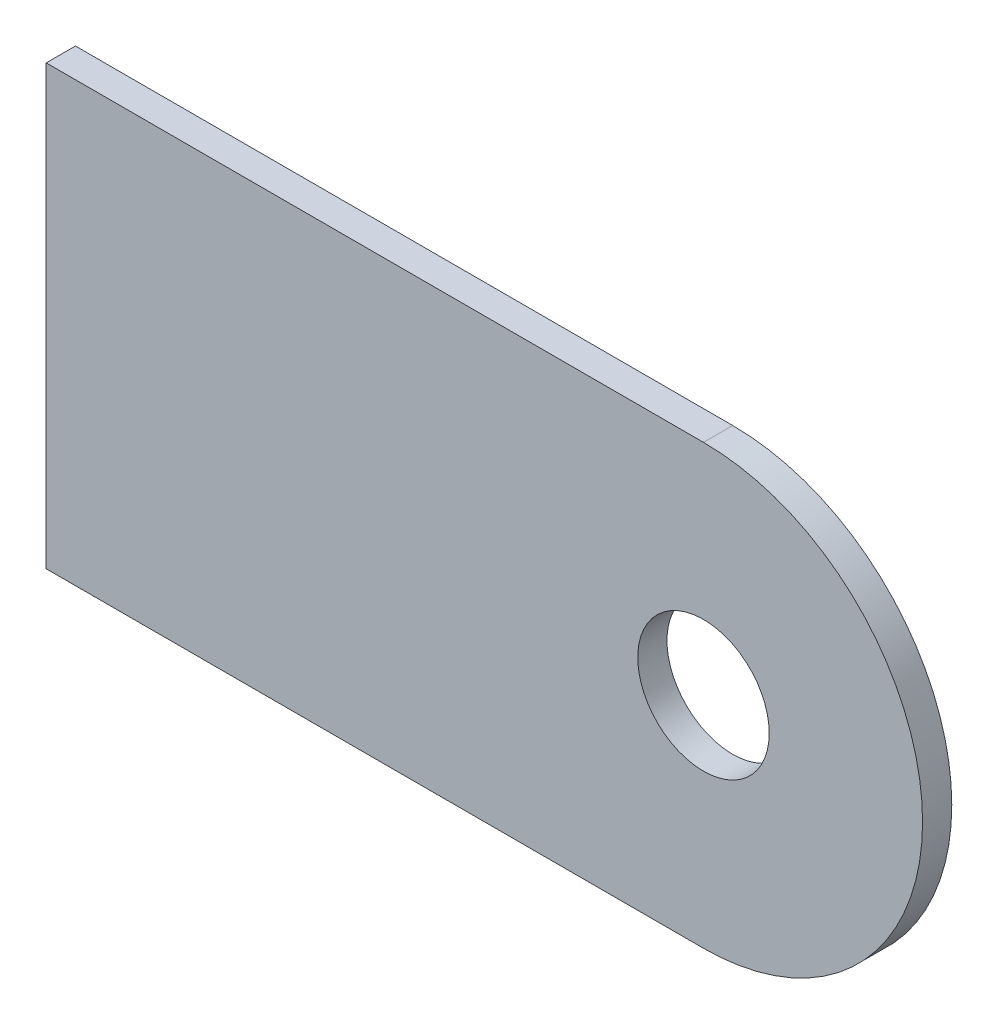
SolidWorks part; units mm, degrees
ref_plane "前视基准面" through (0, 0, 0) normal (0, 0, 1) x (1, 0, 0)
ref_plane "上视基准面" through (0, 0, 0) normal (0, 1, 0) x (1, 0, 0)
ref_plane "右视基准面" through (0, 0, 0) normal (1, 0, 0) x (0, 0, -1)
other "Configuration Table"
sketch "草图1" plane through (0, 0, 0) normal (0, 0, 1) x (1, 0, 0)
  line L0 (0, 30) -> (-90, 30)
  line L1 (-90, 30) -> (-90, -30)
  line L6 (0, -30) -> (-90, -30)
  arc A0 (0, -30) -> (0, 30) centre (0, 0) ccw
  circle A1 centre (0, 0) radius 9
  dimension "D1" = 30
  dimension "D2" = 18
  dimension "D3" = 90
extrude "凸台-拉伸1" add sketch "草图1" along normal blind 4
